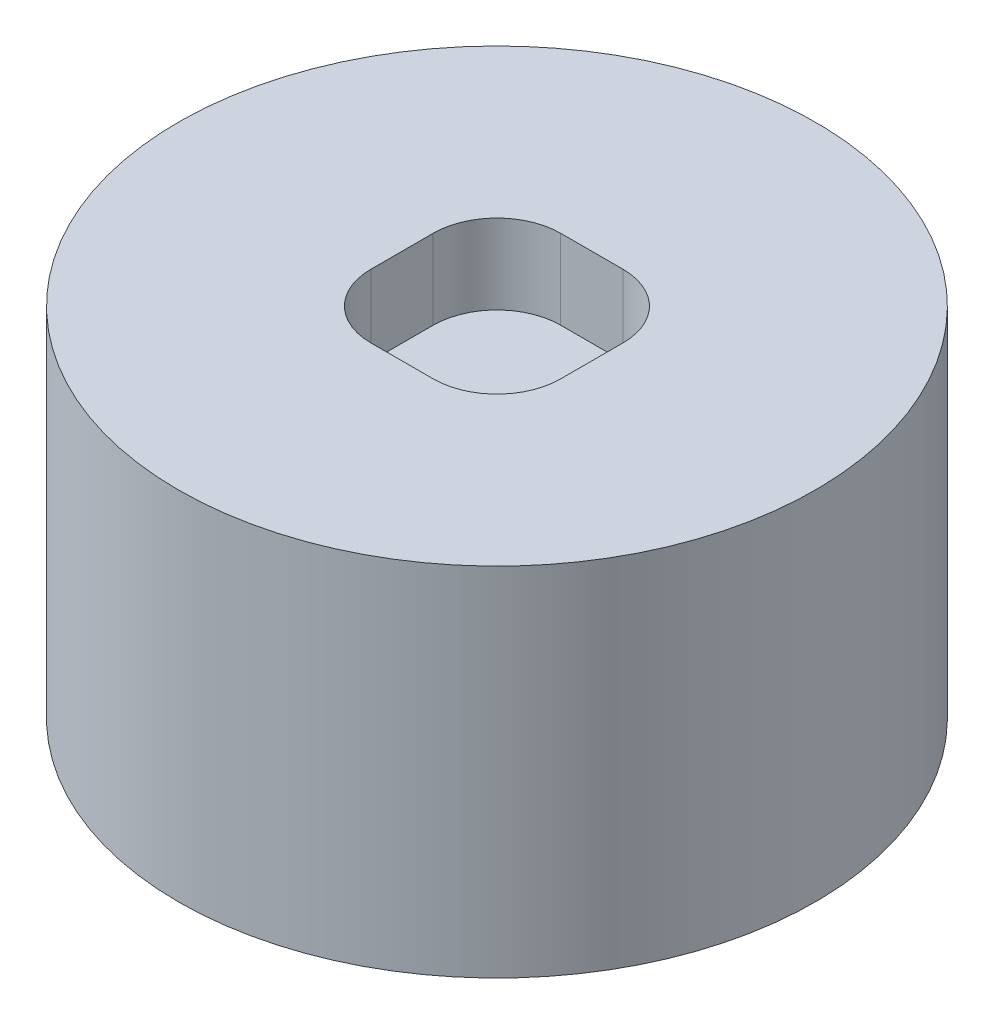
SolidWorks part; units mm, degrees
ref_plane "Front Plane" through (0, 0, 0) normal (0, 0, 1) x (1, 0, 0)
ref_plane "Top Plane" through (0, 0, 0) normal (0, 1, 0) x (1, 0, 0)
ref_plane "Right Plane" through (0, 0, 0) normal (1, 0, 0) x (0, 0, -1)
sketch "Sketch1" plane through (0, 0, 0) normal (0, 1, 0) x (1, 0, 0)
  circle A0 centre (0, 0) radius 10
  circle A1 centre (0, 0) radius 8.985
  dimension "D1" = 20
  dimension "D2" = 17.97
extrude "Boss-Extrude1" add sketch "Sketch1" along normal blind 0.7
sketch "Sketch2" plane through (0, 0.7, 0) normal (0, 1, 0) x (1, 0, 0)
  circle A0 centre (0, 0) radius 10
  circle A1 centre (0, 0) radius 6
  dimension "D1" = 12
extrude "Boss-Extrude2" add sketch "Sketch2" along normal blind 7
sketch "Sketch3" plane through (0, 7.7, 0) normal (0, 1, 0) x (1, 0, 0)
  circle A0 centre (0, 0) radius 10
extrude "Boss-Extrude3" add sketch "Sketch3" along normal blind 1
sketch "Sketch4" plane through (0, 8.7, 0) normal (0, 1, 0) x (1, 0, 0)
  line L1 (-0.98, 2.98) -> (0.98, 2.98)
  line L2 (-2.98, 0.98) -> (-2.98, -0.98)
  line L3 (-0.98, -2.98) -> (0.98, -2.98)
  line L4 (2.98, 0.98) -> (2.98, -0.98)
  line L5 (-2.98, 2.98) -> (2.98, -2.98) construction
  line L6 (-2.98, -2.98) -> (2.98, 2.98) construction
  circle A0 centre (0, 0) radius 10
  arc A1 (-2.98, -0.98) -> (-0.98, -2.98) centre (-0.98, -0.98) ccw
  arc A2 (0.98, -2.98) -> (2.98, -0.98) centre (0.98, -0.98) ccw
  arc A3 (0.98, 2.98) -> (2.98, 0.98) centre (0.98, 0.98) cw
  arc A4 (-0.98, 2.98) -> (-2.98, 0.98) centre (-0.98, 0.98) ccw
  dimension "D1" = 5.96
  dimension "D3" = 2
  dimension "D2" = 5.96
extrude "Boss-Extrude4" add sketch "Sketch4" along normal blind 2.5
